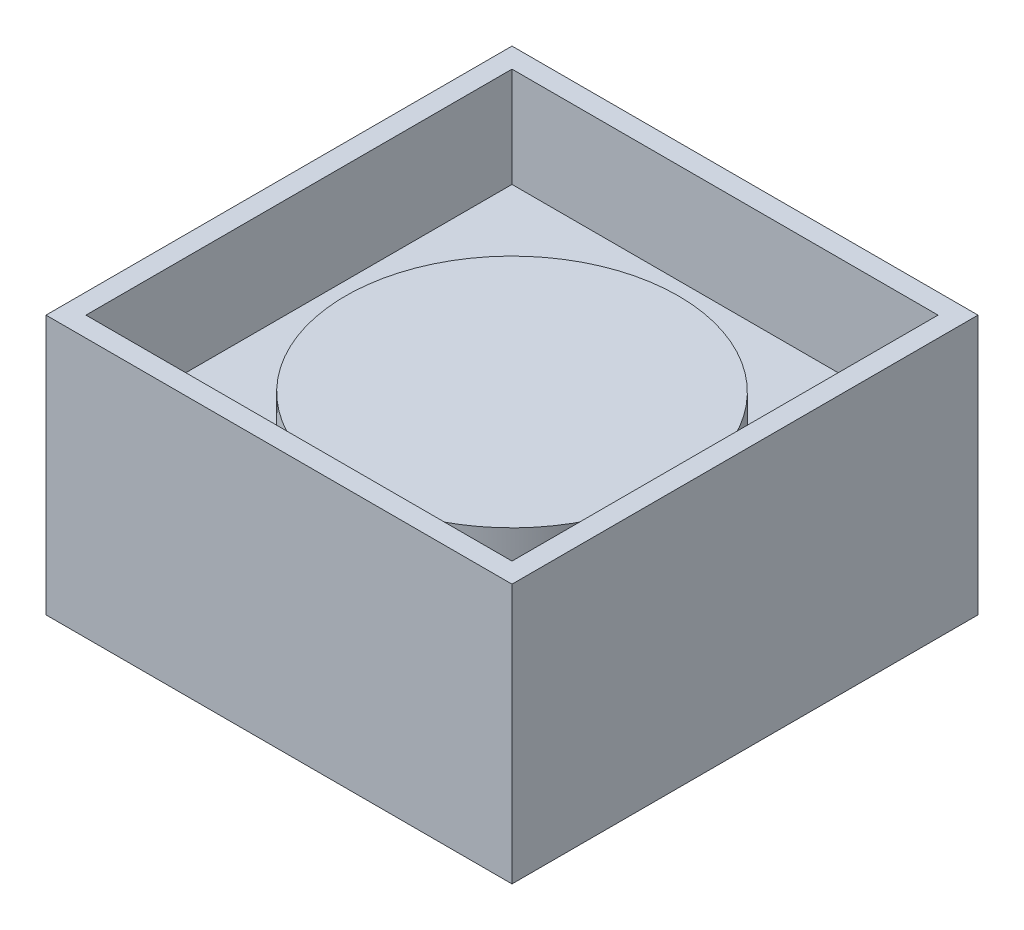
SolidWorks part; units mm, degrees
ref_plane "Front Plane" through (0, 0, 0) normal (0, 0, 1) x (1, 0, 0)
ref_plane "Top Plane" through (0, 0, 0) normal (0, 1, 0) x (1, 0, 0)
ref_plane "Right Plane" through (0, 0, 0) normal (1, 0, 0) x (0, 0, -1)
sketch "Sketch1" plane through (0, 0, 0) normal (0, 1, 0) x (1, 0, 0)
  line L1 (35, 35) -> (-35, 35)
  line L2 (35, 35) -> (35, -35)
  line L3 (35, -35) -> (-35, -35)
  line L4 (-35, 35) -> (-35, -35)
  line L5 (35, 35) -> (-35, -35) construction
  line L6 (35, -35) -> (-35, 35) construction
  point P0 (0, 0)
  dimension "D1" = 70
  dimension "D2" = 70
extrude "Boss-Extrude1" add sketch "Sketch1" along normal blind 39
sketch "Sketch2" plane through (0, 39, 0) normal (0, 1, 0) x (1, 0, 0)
  line L0 (35, -35) -> (35, 35) construction
  line L1 (32, 32) -> (-32, 32)
  line L2 (32, 32) -> (32, -32)
  line L3 (32, -32) -> (-32, -32)
  line L4 (-32, 32) -> (-32, -32)
  line L5 (32, 32) -> (-32, -32) construction
  line L6 (32, -32) -> (-32, 32) construction
  line L7 (-35, -35) -> (35, -35) construction
  point P0 (0, 0)
  dimension "D1" = 3
  dimension "D2" = 3
extrude "Cut-Extrude1" cut sketch "Sketch2" against normal blind 15
sketch "Sketch3" plane through (0, 24, 0) normal (0, 1, 0) x (1, 0, 0)
  circle A0 centre (0, 0) radius 25
extrude "Boss-Extrude2" add sketch "Sketch3" along normal blind 5
